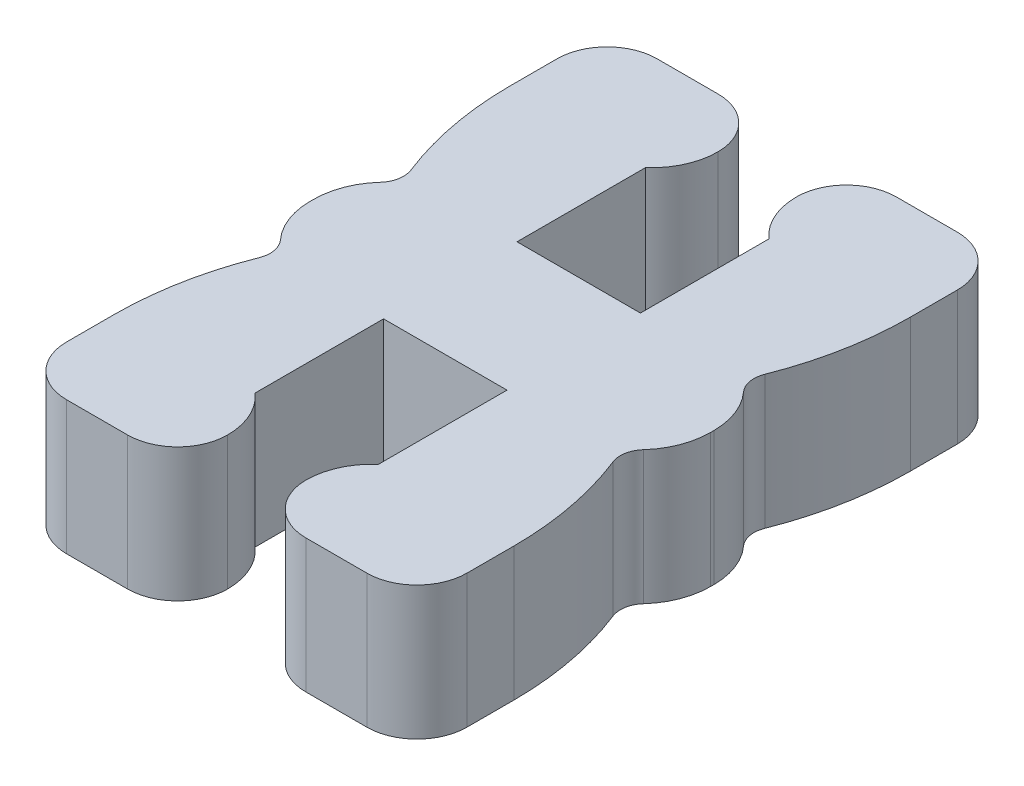
SolidWorks part; units mm, degrees
ref_plane "Front Plane" through (0, 0, 0) normal (0, 0, 1) x (1, 0, 0)
ref_plane "Top Plane" through (0, 0, 0) normal (0, 1, 0) x (1, 0, 0)
ref_plane "Right Plane" through (0, 0, 0) normal (1, 0, 0) x (0, 0, -1)
sketch "Sketch1" plane through (0, 0, 0) normal (0, 1, 0) x (1, 0, 0)
  line L0 (0, -5.85) -> (0, 5.85)
  line L1 (-6, -5.85) -> (6, -5.85)
  line L2 (-6, -5.85) -> (-6, -2.75)
  line L3 (-6, 5.85) -> (6, 5.85)
  line L4 (6, -5.85) -> (6, -2.75)
  line L5 (-6, -5.85) -> (6, 5.85) construction
  line L6 (-6, 5.85) -> (6, -5.85) construction
  line L7 (-4.4021, 0) -> (4.4021, 0)
  line L8 (-1.85, 5.85) -> (1.85, 5.85)
  line L9 (-1.85, 5.85) -> (-1.85, 2)
  line L10 (-5.25, 2) -> (5.25, 2)
  line L11 (1.85, 5.85) -> (1.85, 2)
  line L12 (1.85, -8.85) -> (1.85, -2)
  line L13 (-5.25, -2) -> (5.25, -2)
  line L14 (-1.85, -8.85) -> (-1.85, -2)
  line L15 (-1.85, 5.85) -> (-1.85, 8.85)
  line L16 (-6, 5.85) -> (6, 5.85)
  line L17 (-6, 5.85) -> (-6, 8.85)
  line L18 (-6, 8.85) -> (6, 8.85)
  line L19 (6, 5.85) -> (6, 8.85)
  line L20 (-6, -5.85) -> (6, -5.85)
  line L21 (-6, -5.85) -> (-6, -8.85)
  line L22 (-6, -8.85) -> (6, -8.85)
  line L23 (6, -5.85) -> (6, -8.85)
  line L24 (1.85, 5.85) -> (1.85, 8.85)
  line L25 (-6, 2.75) -> (-6, 5.85)
  line L26 (-6, -1.25) -> (-6, 1.25)
  line L27 (6, -1.25) -> (6, 1.25)
  line L28 (6, 2.75) -> (6, 5.85)
  arc A0 (-1.85, 8.85) -> (-1.85, 5.85) centre (-3.1729, 7.35) cw
  arc A1 (1.85, 8.85) -> (1.85, 5.85) centre (3.1729, 7.35) ccw
  arc A2 (1.85, -8.85) -> (1.85, -5.85) centre (3.1729, -7.35) cw
  arc A3 (-1.85, -8.85) -> (-1.85, -5.85) centre (-3.1729, -7.35) ccw
  arc A4 (6, 2.75) -> (6, 1.25) centre (6, 2) ccw
  arc A5 (-6, 1.25) -> (-6, 2.75) centre (-6, 2) ccw
  arc A6 (6, -1.25) -> (6, -2.75) centre (6, -2) ccw
  arc A7 (-6, -2.75) -> (-6, -1.25) centre (-6, -2) ccw
  point P0 (0, 0)
  point P9 (0, 0)
  point P13 (0, 5.85)
  point P17 (0, 0)
  dimension "D1" = 12
  dimension "D2" = 4
  dimension "D3" = 3.85
  dimension "D4" = 3
  dimension "D5" = 3
extrude "Boss-Extrude2" add sketch "Sketch1" along normal blind 4
fillet "Fillet1" radius 10 4 edges at (6, 2, 2.75) (6, 2, -2.75) (-6, 2, -2.75) (-6, 2, 2.75)
fillet "Fillet2" radius 2.15 4 edges at (-6, 2, 1.25) (-6, 2, -1.25) (6, 2, -1.25) (6, 2, 1.25)
fillet "Fillet3" radius 1.5 8 edges at (-6, 2, -8.85) (6, 2, -8.85) (6, 2, 8.85) (-6, 2, 8.85) (1.85, 2, 8.85) (-1.85, 2, 8.85) (-1.85, 2, -8.85) (1.85, 2, -8.85)
